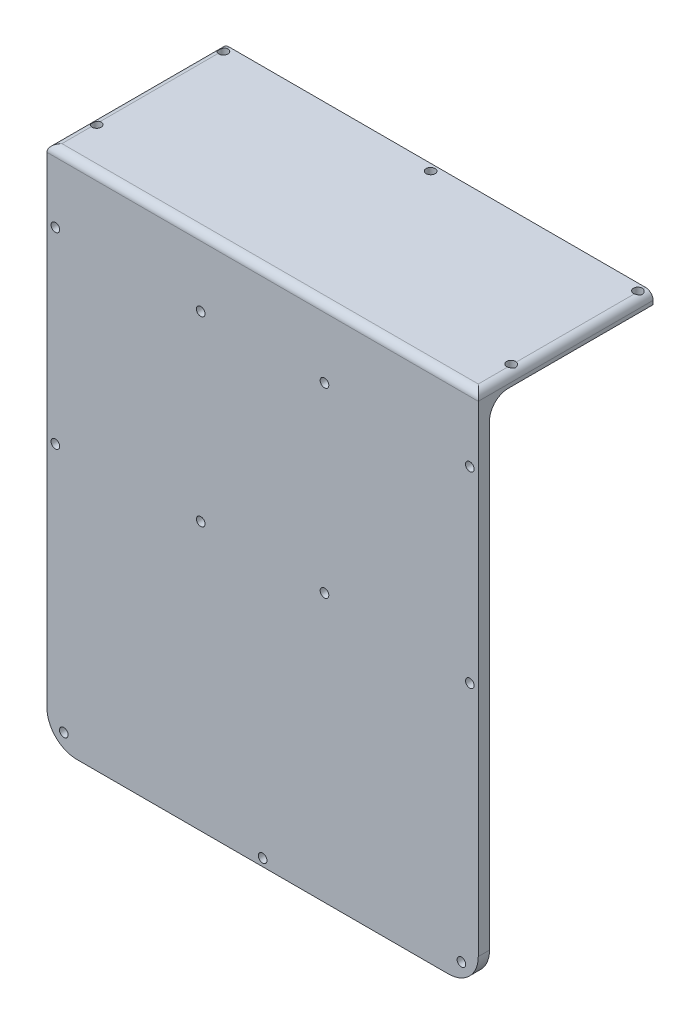
SolidWorks part; units mm, degrees
ref_plane "Front Plane" through (0, 0, 0) normal (0, 0, 1) x (1, 0, 0)
ref_plane "Top Plane" through (0, 0, 0) normal (0, 1, 0) x (1, 0, 0)
ref_plane "Right Plane" through (0, 0, 0) normal (1, 0, 0) x (0, 0, -1)
sketch "Sketch1" plane through (0, 0, 0) normal (0, 0, 1) x (1, 0, 0)
  line L2 (-57.5, 104.3458) -> (57.5, 104.3458)
  line L8 (53, 104.3458) -> (53, -11.4542)
  line L9 (43, -21.4542) -> (-43, -21.4542)
  line L10 (-53, -11.4542) -> (-53, 104.3458)
  line L11 (-53, 104.3458) -> (-57.5, 104.3458)
  line L12 (-57.5, 104.3458) -> (-57.5, -17.4542)
  line L13 (-49.5, -25.4542) -> (49.5, -25.4542)
  line L14 (57.5, -17.4542) -> (57.5, 104.3458)
  line L20 (-57.5, 104.3458) -> (-57.5, -17.4542)
  line L21 (-49.5, -25.4542) -> (49.5, -25.4542)
  line L22 (57.5, -17.4542) -> (57.5, 104.3458)
  line L35 (-53, 104.3458) -> (-57.5, 104.3458)
  line L36 (57.5, 104.3458) -> (53, 104.3458)
  line L37 (57.5, 104.3458) -> (53, 104.3458)
  arc A4 (43, -21.4542) -> (53, -11.4542) centre (43, -11.4542) ccw
  arc A5 (-53, -11.4542) -> (-43, -21.4542) centre (-43, -11.4542) ccw
  arc A6 (-57.5, -17.4542) -> (-49.5, -25.4542) centre (-49.5, -17.4542) ccw
  arc A7 (49.5, -25.4542) -> (57.5, -17.4542) centre (49.5, -17.4542) ccw
  arc A10 (-57.5, -17.4542) -> (-49.5, -25.4542) centre (-49.5, -17.4542) ccw
  arc A11 (49.5, -25.4542) -> (57.5, -17.4542) centre (49.5, -17.4542) ccw
  dimension "D1" = 0
extrude "Boss-Extrude3" add sketch "Sketch1" along normal blind 3 contours L21 A11 L22 L2 L20 A10
other "Move Face1" face at (0, 104.3458, 1.5) parameters "D1"=5.4
sketch "Sketch3" plane through (0, 109.7458, 0) normal (0, 1, 0) x (1, 0, 0)
  line L0 (57.5, -3) -> (57.5, 0) construction
  line L1 (-57.5, -3) -> (57.5, -3)
  line L2 (-57.5, -3) -> (-57.5, 43.6)
  line L3 (-57.5, 43.6) -> (57.5, 43.6)
  line L4 (57.5, -3) -> (57.5, 43.6)
  line L5 (-57.5, 0) -> (57.5, 0) construction
  dimension "D1" = 43.6
extrude "Boss-Extrude4" add sketch "Sketch3" along normal blind 3
fillet "Fillet3" radius 5 1 edges at (0, 109.7458, 0)
fillet "Fillet5" radius 2 3 edges at (57.5, 112.7458, -20.3) (-57.5, 112.7458, -20.3) (0, 112.7458, 3)
sketch "Sketch4" plane through (0, 0, 0) normal (0, 0, -1) x (-1, 0, 0)
  circle A0 centre (-53, -20.9542) radius 1.15
  circle A1 centre (-53, -20.9542) radius 1
  circle A2 centre (-53, -20.9542) radius 1 construction
  circle A3 centre (-55.25, 44.5458) radius 1
  circle A4 centre (-55.25, 44.5458) radius 1 construction
  circle A5 centre (-55.25, 94.5458) radius 1
  circle A6 centre (-55.25, 94.5458) radius 1 construction
  circle A7 centre (0, -23.4542) radius 1
  circle A8 centre (0, -23.4542) radius 1 construction
  circle A9 centre (55.25, 94.5458) radius 1
  circle A10 centre (55.25, 94.5458) radius 1 construction
  circle A11 centre (55.25, 44.5458) radius 1
  circle A12 centre (55.25, 44.5458) radius 1 construction
  circle A13 centre (53, -20.9542) radius 1
  circle A14 centre (53, -20.9542) radius 1 construction
  circle A15 centre (-55.25, 44.5458) radius 1.15
  circle A16 centre (-55.25, 94.5458) radius 1.15
  circle A17 centre (0, -23.4542) radius 1.15
  circle A18 centre (53, -20.9542) radius 1.15
  circle A19 centre (55.25, 44.5458) radius 1.15
  circle A20 centre (55.25, 94.5458) radius 1.15
  dimension "D1" = 0
  dimension "D2" = 0
  dimension "D3" = 0
  dimension "D4" = 0
  dimension "D5" = 0
  dimension "D6" = 0
  dimension "D7" = 0
  dimension "D8" = 0.15
extrude "Cut-Extrude1" cut sketch "Sketch4" against normal through all
sketch "Sketch5" plane through (0, 109.7458, 0) normal (0, -1, 0) x (1, 0, 0)
  circle A0 centre (55.25, -8) radius 1.2
  circle A1 centre (-55.25, -41.8) radius 1.05
  circle A2 centre (-55.25, -41.8) radius 1.05 construction
  circle A3 centre (0, -41.8) radius 1.05
  circle A4 centre (0, -41.8) radius 1.05 construction
  circle A5 centre (55.25, -41.8) radius 1.05
  circle A6 centre (55.25, -41.8) radius 1.05 construction
  circle A7 centre (55.25, -8) radius 1.05
  circle A8 centre (55.25, -8) radius 1.05 construction
  circle A9 centre (-55.25, -8) radius 1.05
  circle A10 centre (-55.25, -8) radius 1.05 construction
  circle A11 centre (55.25, -41.8) radius 1.2
  circle A12 centre (0, -41.8) radius 1.2
  circle A13 centre (-55.25, -8) radius 1.2
  circle A14 centre (-55.25, -41.8) radius 1.2
  dimension "D1" = 0
  dimension "D2" = 0
  dimension "D3" = 0
  dimension "D4" = 0
  dimension "D5" = 0
  dimension "D6" = 0.15
extrude "Cut-Extrude2" cut sketch "Sketch5" against normal through all
sketch "Sketch6" plane through (0, 0, 0) normal (0, 0, -1) x (-1, 0, 0)
  line L13 (57.65, 110.8958) -> (-57.65, 110.8958)
  line L14 (57.65, -17.4542) -> (57.65, 110.8958)
  line L15 (-49.5, -25.6042) -> (49.5, -25.6042)
  circle A1 centre (-16.5, 46) radius 1
  circle A2 centre (-16.5, 46) radius 1 construction
  circle A3 centre (-16.5, 94.5) radius 1
  circle A4 centre (-16.5, 94.5) radius 1 construction
  circle A5 centre (16.5, 94.5) radius 1
  circle A6 centre (16.5, 94.5) radius 1 construction
  circle A7 centre (16.5, 46) radius 1
  circle A8 centre (16.5, 46) radius 1 construction
  circle A10 centre (-16.5, 46) radius 1.15
  circle A11 centre (16.5, 46) radius 1.15
  arc A14 (49.5, -25.6042) -> (57.65, -17.4542) centre (49.5, -17.4542) ccw
  arc A15 (-57.65, -17.4542) -> (-49.5, -25.6042) centre (-49.5, -17.4542) ccw
  circle A16 centre (16.5, 94.5) radius 1.15
  circle A17 centre (-16.5, 94.5) radius 1.15
  dimension "D1" = 0
  dimension "D2" = 0
  dimension "D3" = 0
  dimension "D4" = 0
  dimension "D6" = 0.15
extrude "Cut-Extrude6" cut sketch "Sketch6" against normal through all contours A10 | A11 | A17 | A16
